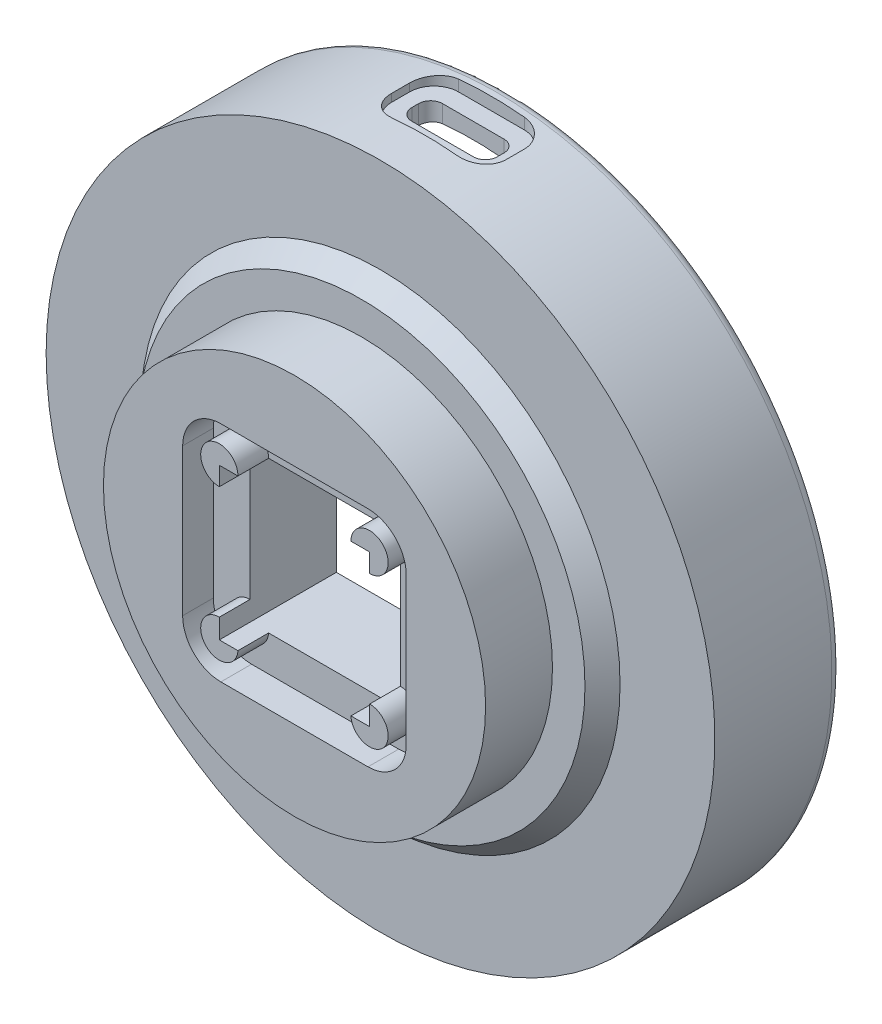
SolidWorks part; units mm, degrees
ref_plane "前视基准面" through (0, 0, 0) normal (0, 0, 1) x (1, 0, 0)
ref_plane "上视基准面" through (0, 0, 0) normal (0, 1, 0) x (1, 0, 0)
ref_plane "右视基准面" through (0, 0, 0) normal (1, 0, 0) x (0, 0, -1)
other "Configuration Table"
ref_plane "基准面1" through (0, 0, 0) normal (0, 0, 1) x (1, 0, 0)
sketch "草图2" plane through (0, 0, 0) normal (0, 0, 1) x (1, 0, 0)
  circle A0 centre (0, 0) radius 20
extrude "凸台-拉伸1" add sketch "草图2" against normal blind 10
sketch "草图3" plane through (0, 0, 0) normal (0, 0, 1) x (1, 0, 0)
  line L0 (-7.7103, 11.7575) -> (7.6897, 11.7575)
  line L1 (11.6897, 7.7575) -> (11.6897, -7.6425)
  line L2 (7.6897, -11.6425) -> (-7.7103, -11.6425)
  line L3 (-11.7103, -7.6425) -> (-11.7103, 7.7575)
  circle A0 centre (7.8497, -7.8025) radius 1.95
  circle A1 centre (7.8497, 7.9175) radius 1.95
  circle A2 centre (-7.8703, 7.9175) radius 1.95
  circle A3 centre (-7.8703, -7.8025) radius 1.95
  arc A4 (-11.7103, -7.6425) -> (-7.7103, -11.6425) centre (-7.7103, -7.6425) ccw
  arc A5 (7.6897, -11.6425) -> (11.6897, -7.6425) centre (7.6897, -7.6425) ccw
  arc A6 (11.6897, 7.7575) -> (7.6897, 11.7575) centre (7.6897, 7.7575) ccw
  arc A7 (-7.7103, 11.7575) -> (-11.7103, 7.7575) centre (-7.7103, 7.7575) ccw
  point P13 (10.5181, -10.4709)
extrude "切除-拉伸1" cut sketch "草图3" against normal up to surface (3.21 mm away)
sketch "草图4" plane through (0, 0, -3.21) normal (0, 0, -1) x (-1, 0, 0)
  circle A0 centre (7.8703, 7.9175) radius 1.95 construction
  circle A1 centre (7.8703, -7.8025) radius 1.95 construction
  circle A2 centre (-7.8497, -7.8025) radius 1.95 construction
  circle A3 centre (-7.8497, 7.9175) radius 1.95 construction
  circle A4 centre (7.8703, 7.9175) radius 1.95
  circle A5 centre (7.8703, -7.8025) radius 1.95
  circle A6 centre (-7.8497, -7.8025) radius 1.95
  circle A7 centre (-7.8497, 7.9175) radius 1.95
extrude "凸台-拉伸2" add sketch "草图4" against normal up to surface (3.21 mm away) up to face at (-0.0103, 0.0575, 0)
sketch "草图5" plane through (0, 0, -3.21) normal (0, 0, -1) x (-1, 0, 0)
  line L1 (-7.8703, -7.9175) -> (7.8703, -7.9175)
  line L2 (-7.8703, -7.9175) -> (-7.8703, 7.9175)
  line L3 (-7.8703, 7.9175) -> (7.8703, 7.9175)
  line L4 (7.8703, -7.9175) -> (7.8703, 7.9175)
  line L5 (-7.8703, -7.9175) -> (7.8703, 7.9175) construction
  line L6 (-7.8703, 7.9175) -> (7.8703, -7.9175) construction
  point P0 (0, 0)
sketch "草图10" plane through (0, 0, 0) normal (0, 1, 0) x (1, 0, 0)
  line L0 (-20, 7) -> (-23.4009, 7)
  line L2 (25.7, 7) -> (-25.7, 7) construction
  line L3 (-20, 10) -> (-20, 0) construction
  line L5 (-23.4009, 10) -> (-25.9121, 10)
  line L6 (-25.9121, 10) -> (-23.4009, 7)
  line L7 (-23.4009, 10) -> (-20, 10)
  line L8 (20, 10) -> (-20, 10) construction
  line L9 (-20, 10) -> (-20, 7)
  line L10 (0, 0) -> (0, 16.4721) construction
  dimension "D1" = 3.9123
revolve "旋转1" add sketch "草图10" angle 360 about L10
sketch "草图11" plane through (0, 0, -10) normal (0, 0, -1) x (-1, 0, 0)
  circle A0 centre (0, 0) radius 35
extrude "凸台-拉伸5" add sketch "草图11" along normal blind 12.25 and the other way blind 1
sketch "草图14" plane through (0, 0, -22.25) normal (0, 0, -1) x (-1, 0, 0)
  circle A0 centre (0, 0) radius 32
extrude "切除-拉伸3" cut sketch "草图14" against normal blind 10
sketch "草图15" plane through (0, 0, -22.25) normal (0, 0, -1) x (-1, 0, 0)
  circle A0 centre (0, 0) radius 33
extrude "切除-拉伸4" cut sketch "草图15" against normal blind 2
ref_plane "基准面2" through (0, 32.1691, 0) normal (0, 1, 0) x (1, 0, 0)
ref_plane "基准面3" through (0, 33.6691, 0) normal (0, 1, 0) x (1, 0, 0)
sketch "草图18" plane through (0, 33.6691, 0) normal (0, 1, 0) x (1, 0, 0)
  line L0 (3.22, 15.9) -> (-3.22, 15.9) construction
  line L1 (-3.22, 18.31) -> (3.22, 18.31) construction
  line L2 (3.22, 15.9) -> (-3.22, 15.9) construction
  line L3 (-3.22, 18.31) -> (3.22, 18.31) construction
  line L4 (-3.22, 15.9) -> (3.22, 18.31) construction
  line L5 (-3.22, 18.31) -> (3.22, 15.9) construction
  line L7 (-3.4462, 13.605) -> (3.4462, 13.605)
  line L8 (-6, 16.1588) -> (-6, 18.0512)
  line L9 (-3.4462, 20.605) -> (3.4462, 20.605)
  line L10 (6, 16.1588) -> (6, 18.0512)
  line L11 (-6, 13.605) -> (6, 20.605) construction
  line L12 (-6, 20.605) -> (6, 13.605) construction
  arc A3 (-6, 16.1588) -> (-3.4462, 13.605) centre (-3.4462, 16.1588) ccw
  arc A4 (6, 18.0512) -> (3.4462, 20.605) centre (3.4462, 18.0512) ccw
  arc A5 (-3.4462, 20.605) -> (-6, 18.0512) centre (-3.4462, 18.0512) ccw
  arc A6 (3.4462, 13.605) -> (6, 16.1588) centre (3.4462, 16.1588) ccw
  point P4 (0, 17.105)
  dimension "D1" = 7
  dimension "D2" = 12
extrude "切除-拉伸5" cut sketch "草图18" along normal blind 10
sketch "草图19" plane through (0, 32.1691, 0) normal (0, 1, 0) x (1, 0, 0)
  line L0 (-4.47, 16.75) -> (-4.47, 17.46) construction
  line L1 (3.22, 15.5) -> (-3.22, 15.5) construction
  line L2 (4.47, 17.46) -> (4.47, 16.75) construction
  line L3 (-3.22, 18.71) -> (3.22, 18.71) construction
  line L4 (-4.47, 16.75) -> (-4.47, 17.46)
  line L5 (3.22, 15.5) -> (-3.22, 15.5)
  line L6 (4.47, 17.46) -> (4.47, 16.75)
  line L7 (-3.22, 18.71) -> (3.22, 18.71)
  arc A0 (-3.22, 18.71) -> (-4.47, 17.46) centre (-3.22, 17.46) ccw construction
  arc A1 (-4.47, 16.75) -> (-3.22, 15.5) centre (-3.22, 16.75) ccw construction
  arc A2 (3.22, 15.5) -> (4.47, 16.75) centre (3.22, 16.75) ccw construction
  arc A3 (4.47, 17.46) -> (3.22, 18.71) centre (3.22, 17.46) ccw construction
  arc A4 (-3.22, 18.71) -> (-4.47, 17.46) centre (-3.22, 17.46) ccw
  arc A5 (-4.47, 16.75) -> (-3.22, 15.5) centre (-3.22, 16.75) ccw
  arc A6 (3.22, 15.5) -> (4.47, 16.75) centre (3.22, 16.75) ccw
  arc A7 (4.47, 17.46) -> (3.22, 18.71) centre (3.22, 17.46) ccw
extrude "切除-拉伸6" cut sketch "草图19" along normal blind 2 and the other way blind 2
sketch "草图21" plane through (0, 0, -12.25) normal (0, 0, -1) x (-1, 0, 0)
  line L0 (14.199, 7.7763) -> (12.0967, 10.9382)
  line L1 (14.199, 7.7763) -> (12.8395, 6.8724)
  line L2 (12.0967, 10.9382) -> (10.7372, 10.0343)
  line L3 (12.8395, 6.8724) -> (10.7372, 10.0343)
  line L4 (11.4258, 11.9472) -> (14.7479, 6.9509) construction
  line L5 (13.985, 13.6489) -> (12.1459, 12.4261)
  line L6 (13.985, 13.6489) -> (13.1428, 14.9156)
  line L7 (12.1459, 12.4261) -> (11.3037, 13.6928)
  line L8 (13.1428, 14.9156) -> (11.3037, 13.6928)
  line L9 (14.3403, 13.8851) -> (11.4258, 11.9472) construction
  line L10 (17.3071, 8.6525) -> (15.3591, 7.3572)
  line L11 (17.3071, 8.6525) -> (18.292, 7.1713)
  line L12 (15.3591, 7.3572) -> (16.3439, 5.8761)
  line L13 (18.292, 7.1713) -> (16.3439, 5.8761)
  line L14 (17.6624, 8.8888) -> (14.7479, 6.9509) construction
extrude "凸台-拉伸6" add sketch "草图21" along normal blind 2
sketch "草图23" plane through (0, 0, -12.25) normal (0, 0, -1) x (-1, 0, 0)
  line L0 (25.2665, 12.3601) -> (20.6605, 19.4634)
  line L1 (25.2665, 12.3601) -> (21.2299, 9.7427)
  line L2 (20.6605, 19.4634) -> (16.624, 16.8461)
  line L3 (21.2299, 9.7427) -> (16.624, 16.8461)
extrude "凸台-拉伸9" add sketch "草图23" along normal up to vertex (0.4572 mm away)
ref_plane "基准面4" through (-23.43, 15.1923, 0) normal (-0.8391, 0.5441, 0) x (0, 0, 1)
sketch "草图24" plane through (-23.43, 15.1923, 0) normal (-0.8391, 0.5441, 0) x (0, 0, 1)
  line L0 (-14.0496, 3.0642) -> (-14.0496, -1.0091) construction
  line L1 (-14.0496, 3.0642) -> (-14.0496, -1.0091)
  line L2 (-15.6128, 4.6273) -> (-15.6128, -2.5722)
  spline S0 degree 3 poles (3468.207, -1953.2538) (-155.8363, -103.4585) (-23.8619, 13.5233) (-5.153, -5.1844) (-122.1435, -137.151) (-1972.0825, 3486.6955) knots -15.662792 -15.662792 -15.662792 -15.662792 0.5 0.5 16.662856 16.662856 16.662856 16.662856 only from (-15.6128, 4.6273) to (-14.0496, 3.0642) construction
  spline S1 degree 3 poles (-1972.1521, -3484.7767) (-122.1465, 139.2095) (-5.1529, 7.2396) (-23.8619, -11.4682) (-155.8361, 105.5134) (3468.1961, 1955.3033) knots -15.663059 -15.663059 -15.663059 -15.663059 0.5 0.5 16.662776 16.662776 16.662776 16.662776 only from (-14.0496, -1.0091) to (-15.6128, -2.5722) construction
  spline S2 degree 3 poles (-15.6128, 4.6273) (-15.2036, 4.6273) (-14.7968, 4.4589) (-14.2181, 3.8801) (-14.0496, 3.4734) (-14.0496, 3.0642) knots 0 0 0 0 0.5 0.5 1 1 1 1
  spline S3 degree 3 poles (-14.0496, -1.0091) (-14.0496, -1.4183) (-14.2181, -1.825) (-14.7968, -2.4037) (-15.2036, -2.5722) (-15.6128, -2.5722) knots 0 0 0 0 0.5 0.5 1 1 1 1
extrude "切除-拉伸8" cut sketch "草图24" against normal blind 5
sketch "草图25" plane through (0, 0, 0) normal (0, 0, 1) x (1, 0, 0)
  line L1 (-7.8703, -7.9175) -> (7.8703, -7.9175)
  line L2 (-7.8703, -7.9175) -> (-7.8703, 7.9175)
  line L3 (-7.8703, 7.9175) -> (7.8703, 7.9175)
  line L4 (7.8703, -7.9175) -> (7.8703, 7.9175)
  line L5 (-7.8703, -7.9175) -> (7.8703, 7.9175) construction
  line L6 (-7.8703, 7.9175) -> (7.8703, -7.9175) construction
  point P0 (0, 0)
extrude "切除-拉伸9" cut sketch "草图25" against normal blind 15
sketch "草图26" plane through (0, 0, -12.25) normal (0, 0, -1) x (-1, 0, 0)
  line L0 (9.7441, -20.9213) -> (-6.2698, -20.861)
  line L1 (9.7441, -20.9213) -> (9.7383, -22.4771)
  line L2 (-6.2698, -20.861) -> (-6.2757, -22.4169)
  line L3 (9.7383, -22.4771) -> (-6.2757, -22.4169)
  line L4 (-19.2352, -20.861) -> (20.7648, -20.861) construction
  line L5 (-19.2352, -15.2447) -> (-19.2352, -3.294)
  line L6 (-19.2352, -15.2447) -> (-20.7302, -15.2447)
  line L7 (-19.2352, -3.294) -> (-20.7302, -3.294)
  line L8 (-20.7302, -15.2447) -> (-20.7302, -3.294)
  line L9 (-19.2352, 4.139) -> (-19.2352, -20.861) construction
  line L15 (12.6149, 4.139) -> (7.8703, 4.139)
  line L16 (12.6149, 4.139) -> (12.6149, 5.7075)
  line L17 (7.8703, 4.139) -> (7.8703, 5.7075)
  line L18 (12.6149, 5.7075) -> (7.8703, 5.7075)
  line L19 (20.7648, 4.139) -> (-19.2352, 4.139) construction
  line L20 (7.8703, -7.9175) -> (7.8703, 7.9175) construction
  line L21 (-7.8703, 4.139) -> (-14.8848, 4.139)
  line L22 (-7.8703, 4.139) -> (-7.8703, 5.6925)
  line L23 (-14.8848, 4.139) -> (-14.8848, 5.6925)
  line L24 (-7.8703, 5.6925) -> (-14.8848, 5.6925)
  line L25 (22.3515, -3.0098) -> (22.3515, -11.3652)
  line L26 (-7.8703, -7.9175) -> (-7.8703, 7.9175) construction
  line L27 (22.3515, -11.3652) -> (24.1513, -11.3652)
  line L28 (24.1513, -11.3652) -> (24.1513, -3.0098)
  line L29 (22.3515, -3.0098) -> (24.1513, -3.0098)
  circle A0 centre (0, 0) radius 25.0751 construction
extrude "凸台-拉伸10" add sketch "草图26" along normal up to surface (8 mm away) up to face at (-33, 0, -20.25)
sketch "草图28" plane through (0, 0, -12.25) normal (0, 0, -1) x (-1, 0, 0)
  line L8 (4.473, 14.3082) -> (-0.8944, 14.3082)
  line L9 (-0.8944, 14.3082) -> (-0.8944, 22.1473)
  line L10 (-0.8944, 22.1473) -> (4.473, 22.1473)
  line L11 (4.473, 22.1473) -> (4.473, 14.3082)
extrude "凸台-拉伸11" add sketch "草图28" along normal up to surface (2 mm away)
sketch "草图29" plane through (0, 0, -12.25) normal (0, 0, -1) x (-1, 0, 0)
  line L5 (8.8973, 13.7512) -> (8.8973, 26.6236)
  line L6 (8.8973, 13.7512) -> (10.5973, 13.7512)
  line L7 (8.8973, 26.6236) -> (10.5973, 26.6236)
  line L8 (10.5973, 13.7512) -> (10.5973, 26.6236)
  line L9 (8.8973, 14.2592) -> (8.8973, 13.2432) construction
  line L10 (8.8973, 26.9592) -> (8.8973, 25.9432) construction
  line L11 (-8.8827, 13.7512) -> (-8.8827, 26.4512)
  line L12 (-8.8827, 13.7512) -> (-10.5827, 13.7512)
  line L13 (-8.8827, 26.4512) -> (-10.5827, 26.4512)
  line L14 (-10.5827, 13.7512) -> (-10.5827, 26.4512)
  line L15 (-8.8827, 13.2432) -> (-8.8827, 14.2592) construction
  line L16 (-8.8827, 25.9432) -> (-8.8827, 26.9592) construction
  line L17 (6.2063, 9.6872) -> (0.4247, 9.6872)
  line L18 (6.2063, 9.6872) -> (6.2063, 7.9538)
  line L19 (0.4247, 9.6872) -> (0.4247, 7.9538)
  line L20 (6.2063, 7.9538) -> (0.4247, 7.9538)
  line L21 (6.9923, 9.6872) -> (-6.9777, 9.6872) construction
extrude "凸台-拉伸12" add sketch "草图29" along normal up to surface (3.25 mm away)
sketch "草图30" plane through (0, 0, -12.25) normal (0, 0, -1) x (-1, 0, 0)
  line L0 (15.6297, 20.6049) -> (15.6297, 25.6049)
  line L1 (15.6297, 20.6049) -> (17.1744, 20.6049)
  line L2 (15.6297, 25.6049) -> (17.1744, 25.6049)
  line L3 (17.1744, 20.6049) -> (17.1744, 25.6049)
  line L4 (15.6297, 25.6049) -> (15.6297, 20.6049) construction
  line L5 (15.6297, 20.6049) -> (10.6297, 20.6049) construction
  line L6 (-16.6295, 17.4342) -> (-16.6408, 21.5304)
  line L7 (-16.6295, 17.4342) -> (-18.3625, 17.4295)
  line L8 (-16.6408, 21.5304) -> (-18.3737, 21.5257)
  line L9 (-18.3625, 17.4295) -> (-18.3737, 21.5257)
  line L10 (-16.6273, 16.6123) -> (-16.6438, 22.6123) construction
  line L11 (-22.0027, 12.5462) -> (-26.3224, 12.5462)
  line L12 (-22.0027, 12.5462) -> (-22.0027, 14.1786)
  line L13 (-26.3224, 12.5462) -> (-26.3224, 14.1786)
  line L14 (-22.0027, 14.1786) -> (-26.3224, 14.1786)
  line L15 (-27.0914, 12.5462) -> (-21.0914, 12.5462) construction
  line L16 (-26.3224, 18.1969) -> (-26.3224, -18.1969) construction
  line L17 (-22.2065, 6.5462) -> (-26.1811, 6.5462)
  line L18 (-22.2065, 6.5462) -> (-22.2065, 4.8553)
  line L19 (-26.1811, 6.5462) -> (-26.1811, 4.8553)
  line L20 (-22.2065, 4.8553) -> (-26.1811, 4.8553)
  line L21 (-27.0914, 6.5462) -> (-21.0914, 6.5462) construction
extrude "凸台-拉伸13" add sketch "草图30" along normal blind 1.6
sketch "草图32" plane through (-29.6952, 19.7445, 0) normal (-0.8327, 0.5537, 0) x (0, 0, 1)
  line L1 (-14.5496, -1.4143) -> (-14.5496, 2.6593) construction
  line L2 (-17.7272, 2.6593) -> (-17.7272, -1.4143) construction
  line L3 (-15.6128, 3.7225) -> (-16.664, 3.7225) construction
  line L4 (-16.664, -2.4775) -> (-15.6128, -2.4775) construction
  line L5 (-15.6128, 3.7225) -> (-16.664, 3.7225) construction
  line L6 (-17.7272, 2.6593) -> (-17.7272, -1.4143) construction
  line L7 (-16.664, -2.4775) -> (-15.6128, -2.4775) construction
  line L8 (-14.5496, -1.4143) -> (-14.5496, 2.6593) construction
  line L11 (-16.738, -3.0775) -> (-15.5389, -3.0775)
  line L12 (-18.3284, -1.487) -> (-18.3284, 2.7321)
  line L13 (-16.738, 4.3225) -> (-15.5389, 4.3225)
  line L14 (-13.9484, -1.487) -> (-13.9484, 2.7321)
  line L15 (-18.3284, -3.0775) -> (-13.9484, 4.3225) construction
  line L16 (-18.3284, 4.3225) -> (-13.9484, -3.0775) construction
  arc A1 (-16.738, 4.3225) -> (-18.3284, 2.7321) centre (-16.738, 2.7321) ccw
  arc A3 (-15.5389, -3.0775) -> (-13.9484, -1.487) centre (-15.5389, -1.487) ccw
  arc A7 (-13.9484, 2.7321) -> (-15.5389, 4.3225) centre (-15.5389, 2.7321) ccw
  arc A8 (-18.3284, -1.487) -> (-16.738, -3.0775) centre (-16.738, -1.487) ccw
  spline S0 degree 2 poles (-1990.9214, -302.4994) (-1.8097, -27.9035) (-14.6317, 3.066) (-14.7134, 3.2634) (-14.861, 3.4111) (-15.0078, 3.5581) (-15.2061, 3.6404) (-46.0651, 16.4498) (-345.0454, -1968.7383) knots -38.783049 -38.783049 -38.783049 0.25 0.25 0.5 0.5 0.75 0.75 39.744657 39.744657 39.744657 only from (-14.5496, 2.6593) to (-15.6128, 3.7225) construction
  spline S1 degree 2 poles (-14.5496, 2.6593) (-14.5496, 2.8676) (-14.6317, 3.066) (-14.7134, 3.2634) (-14.861, 3.4111) (-15.0078, 3.5581) (-15.2061, 3.6404) (-15.404, 3.7225) (-15.6128, 3.7225) knots 0 0 0 0.25 0.25 0.5 0.5 0.75 0.75 1 1 1 construction
  spline S2 degree 2 poles (288.4947, -1972.6493) (13.8988, 16.4624) (-17.0707, 3.6404) (-17.268, 3.5587) (-17.4158, 3.4111) (-17.5628, 3.2643) (-17.6451, 3.066) (-30.4545, -27.793) (1954.7336, -326.7733) knots -38.783049 -38.783049 -38.783049 0.25 0.25 0.5 0.5 0.75 0.75 39.744657 39.744657 39.744657 only from (-16.664, 3.7225) to (-17.7272, 2.6593) construction
  spline S3 degree 2 poles (1958.6446, 303.7444) (-30.4671, 29.1485) (-17.6451, -1.821) (-17.5634, -2.0183) (-17.4158, -2.1661) (-17.269, -2.3131) (-17.0707, -2.3954) (13.7883, -15.2048) (312.7686, 1969.9834) knots -38.783049 -38.783049 -38.783049 0.25 0.25 0.5 0.5 0.75 0.75 39.744657 39.744657 39.744657 only from (-17.7272, -1.4143) to (-16.664, -2.4775) construction
  spline S4 degree 2 poles (-320.7715, 1973.8943) (-46.1756, -15.2174) (-15.2061, -2.3954) (-15.0088, -2.3137) (-14.861, -2.1661) (-14.714, -2.0193) (-14.6317, -1.821) (-1.8223, 29.038) (-1987.0105, 328.0183) knots -38.783049 -38.783049 -38.783049 0.25 0.25 0.5 0.5 0.75 0.75 39.744657 39.744657 39.744657 only from (-15.6128, -2.4775) to (-14.5496, -1.4143) construction
  spline S5 degree 2 poles (-16.664, 3.7225) (-16.8723, 3.7225) (-17.0707, 3.6404) (-17.268, 3.5587) (-17.4158, 3.4111) (-17.5628, 3.2643) (-17.6451, 3.066) (-17.7272, 2.8682) (-17.7272, 2.6593) knots 0 0 0 0.25 0.25 0.5 0.5 0.75 0.75 1 1 1 construction
  spline S6 degree 2 poles (-17.7272, -1.4143) (-17.7272, -1.6226) (-17.6451, -1.821) (-17.5634, -2.0183) (-17.4158, -2.1661) (-17.269, -2.3131) (-17.0707, -2.3954) (-16.8728, -2.4775) (-16.664, -2.4775) knots 0 0 0 0.25 0.25 0.5 0.5 0.75 0.75 1 1 1 construction
  spline S7 degree 2 poles (-15.6128, -2.4775) (-15.4045, -2.4775) (-15.2061, -2.3954) (-15.0088, -2.3137) (-14.861, -2.1661) (-14.714, -2.0193) (-14.6317, -1.821) (-14.5496, -1.6231) (-14.5496, -1.4143) knots 0 0 0 0.25 0.25 0.5 0.5 0.75 0.75 1 1 1
  point P0 (-16.1384, 0.6225)
  dimension "D1" = 7.4
  dimension "D2" = 4.38
extrude "切除-拉伸11" cut sketch "草图32" against normal blind 5 contours A8 L11 A3 L14 A7 L13 A1 L12
sketch "草图33" plane through (0, 0, -12.25) normal (0, 0, -1) x (-1, 0, 0)
  circle A2 centre (26.0035, 9.2966) radius 1.425
  circle A6 centre (26.0035, 9.2966) radius 2.925
  circle A7 centre (-4.9507, -27.1679) radius 2.925
  circle A8 centre (-4.9507, -27.1679) radius 1.425
  circle A9 centre (-21.0528, 17.8714) radius 2.925
  circle A10 centre (-21.0528, 17.8714) radius 1.425
  dimension "D1" = 3
  dimension "D5" = 2.85
  dimension "D6" = 1.5
extrude "凸台-拉伸15" add sketch "草图33" along normal blind 4
fillet "圆角1" radius 1 1 edges at (-35, 0, -22.25)
